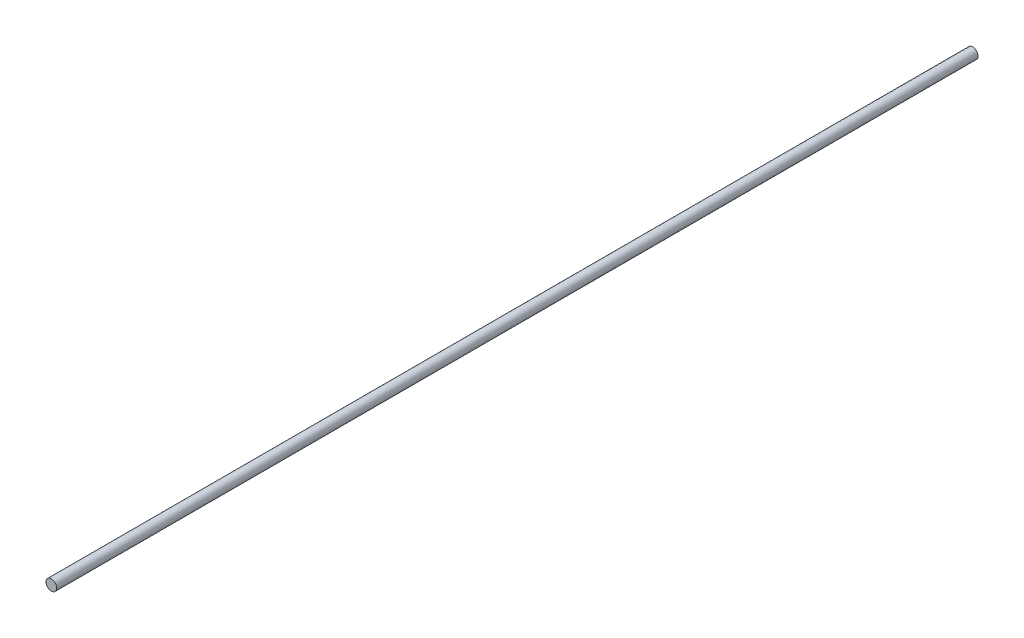
SolidWorks part; units mm, degrees
material "Stainless Steel (ferritic)"
ref_plane "Front Plane" through (0, 0, 0) normal (0, 0, 1) x (1, 0, 0)
ref_plane "Top Plane" through (0, 0, 0) normal (0, 1, 0) x (1, 0, 0)
ref_plane "Right Plane" through (0, 0, 0) normal (1, 0, 0) x (0, 0, -1)
sketch "Sketch1" plane through (0, 0, 0) normal (0, 0, 1) x (1, 0, 0)
  circle A0 centre (0, 0) radius 3
  dimension "D1" = 6
extrude "Boss-Extrude1" add sketch "Sketch1" along normal blind 520
